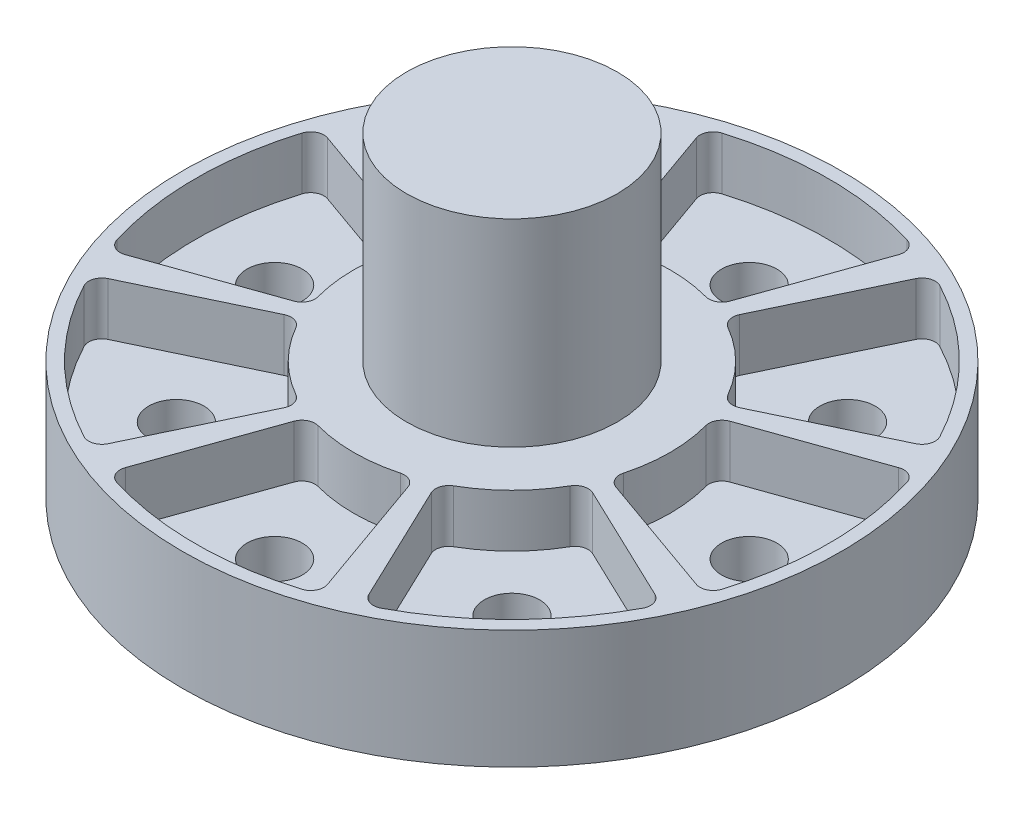
SolidWorks part; units mm, degrees
ref_plane "Спереди" through (0, 0, 0) normal (0, 0, 1) x (1, 0, 0)
ref_plane "Сверху" through (0, 0, 0) normal (0, 1, 0) x (1, 0, 0)
ref_plane "Справа" through (0, 0, 0) normal (1, 0, 0) x (0, 0, -1)
sketch "Эскиз1" plane through (0, 0, 0) normal (0, 1, 0) x (1, 0, 0)
  circle A1 centre (-18, 0) radius 2.1
  circle A2 centre (-12.7279, 12.7279) radius 2.1
  circle A3 centre (0, 18) radius 2.1
  circle A4 centre (12.7279, 12.7279) radius 2.1
  circle A5 centre (18, 0) radius 2.1
  circle A6 centre (12.7279, -12.7279) radius 2.1
  circle A7 centre (0, -18) radius 2.1
  circle A8 centre (-12.7279, -12.7279) radius 2.1
  circle A9 centre (0, 0) radius 25
extrude "Бобышка-Вытянуть1" add sketch "Эскиз1" along normal blind 5
ref_plane "Плоскость1" through (0, 5, 0) normal (0, 1, 0) x (1, 0, 0)
sketch "Эскиз2" plane through (0, 5, 0) normal (0, 1, 0) x (1, 0, 0)
  line L32 (-5.1661, -10.831) -> (-10.3323, -21.662)
  line L33 (-4.0057, -11.3117) -> (-8.0114, -22.6234)
  line L34 (-10.831, -5.1661) -> (-21.662, -10.3323)
  line L35 (-22.6234, -8.0114) -> (-11.3117, -4.0057)
  line L36 (-11.3117, 4.0057) -> (-22.6234, 8.0114)
  line L37 (-21.662, 10.3323) -> (-10.831, 5.1661)
  line L38 (-10.3323, 21.662) -> (-5.1661, 10.831)
  line L39 (-8.0114, 22.6234) -> (-4.0057, 11.3117)
  line L40 (8.0114, 22.6234) -> (4.0057, 11.3117)
  line L41 (10.3323, 21.662) -> (5.1661, 10.831)
  line L42 (10.831, 5.1661) -> (21.662, 10.3323)
  line L43 (11.3117, 4.0057) -> (22.6234, 8.0114)
  line L44 (11.3117, -4.0057) -> (22.6234, -8.0114)
  line L45 (10.831, -5.1661) -> (21.662, -10.3323)
  line L46 (5.1661, -10.831) -> (10.3323, -21.662)
  line L47 (4.0057, -11.3117) -> (8.0114, -22.6234)
  circle A1 centre (0, 0) radius 12
  circle A2 centre (0, 0) radius 25
  circle A4 centre (0, 0) radius 24
extrude "Бобышка-Вытянуть2" add sketch "Эскиз2" along normal blind 4 contours A2 A4 | A1 | L39 A4 L38 A1 | L41 A4 L40 A1 | L43 A4 L42 A1 | L45 A4 L44 A1 | L47 A4 L46 A1 | L32 A4 L33 A1 | L35 A4 L34 A1 | L37 A4 L36 A1
fillet "Скругление1" radius 1 32 edges at (-4.0057, 7, -11.3117) (4.0057, 7, -11.3117) (8.0114, 7, -22.6234) (-8.0114, 7, -22.6234) (21.662, 7, -10.3323) (10.3323, 7, -21.662) (5.1661, 7, -10.831) (10.831, 7, -5.1661) (22.6234, 7, -8.0114) (11.3117, 7, -4.0057) (11.3117, 7, 4.0057) (22.6234, 7, 8.0114) (21.662, 7, 10.3323) (10.831, 7, 5.1661) (5.1661, 7, 10.831) (10.3323, 7, 21.662) (8.0114, 7, 22.6234) (4.0057, 7, 11.3117) (-4.0057, 7, 11.3117) (-8.0114, 7, 22.6234) (-10.3323, 7, 21.662) (-5.1661, 7, 10.831) (-10.831, 7, 5.1661) (-21.662, 7, 10.3323) (-11.3117, 7, 4.0057) (-11.3117, 7, -4.0057) (-22.6234, 7, 8.0114) (-22.6234, 7, -8.0114) (-10.831, 7, -5.1661) (-5.1661, 7, -10.831) (-21.662, 7, -10.3323) (-10.3323, 7, -21.662)
ref_plane "Плоскость2" through (0, 9, 0) normal (0, 1, 0) x (1, 0, 0)
sketch "Эскиз3" plane through (0, 9, 0) normal (0, 1, 0) x (1, 0, 0)
  circle A0 centre (0, 0) radius 8
extrude "Бобышка-Вытянуть3" add sketch "Эскиз3" along normal blind 15
